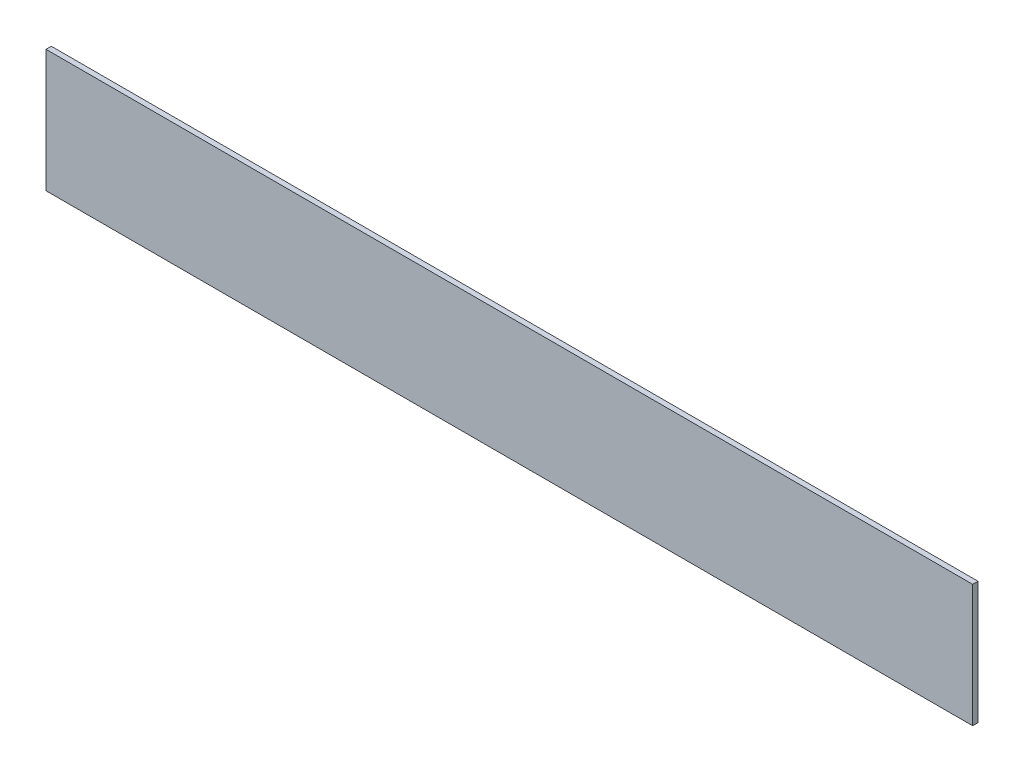
SolidWorks part; units mm, degrees
material "Custom Plastic"
ref_plane "X-Y Datum" through (0, 0, 0) normal (0, 0, 1) x (1, 0, 0)
ref_plane "X-Z Datum" through (0, 0, 0) normal (0, 1, 0) x (1, 0, 0)
ref_plane "Y-Z Datum" through (0, 0, 0) normal (1, 0, 0) x (0, 0, -1)
sketch "Sketch1" plane through (0, 0, 0) normal (0, 0, 1) x (1, 0, 0)
  line L1 (-276.225, 36.5125) -> (276.225, 36.5125)
  line L2 (-276.225, 36.5125) -> (-276.225, -36.5125)
  line L3 (-276.225, -36.5125) -> (276.225, -36.5125)
  line L4 (276.225, 36.5125) -> (276.225, -36.5125)
  line L5 (-276.225, 36.5125) -> (276.225, -36.5125) construction
  line L6 (-276.225, -36.5125) -> (276.225, 36.5125) construction
  point P0 (0, 0)
  dimension "D1" = 552.45
  dimension "D2" = 73.025
extrude "Boss-Extrude1" add sketch "Sketch1" along normal blind 3.175
